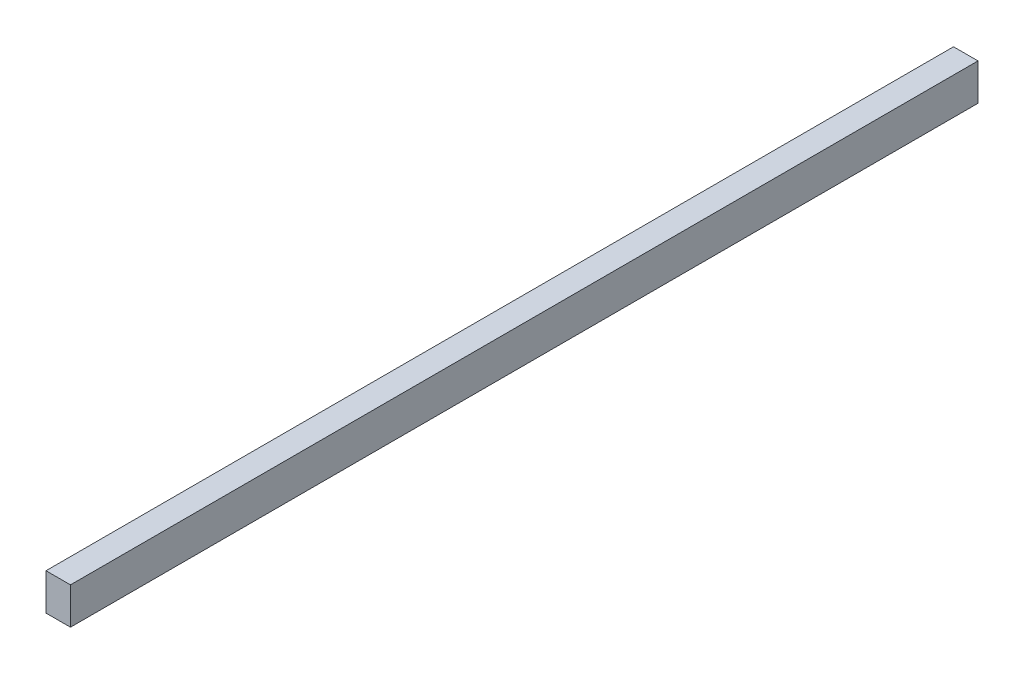
SolidWorks part; units mm, degrees
ref_plane "Front Plane" through (0, 0, 0) normal (0, 0, 1) x (1, 0, 0)
ref_plane "Top Plane" through (0, 0, 0) normal (0, 1, 0) x (1, 0, 0)
ref_plane "Right Plane" through (0, 0, 0) normal (1, 0, 0) x (0, 0, -1)
sketch "Sketch1" plane through (0, 0, 0) normal (1, 0, 0) x (0, 0, -1)
  line L1 (0, 0) -> (445, 0)
  line L2 (0, 0) -> (0, 18)
  line L3 (0, 18) -> (445, 18)
  line L4 (445, 0) -> (445, 18)
  dimension "D1" = 445
  dimension "D2" = 18
extrude "Boss-Extrude1" add sketch "Sketch1" along normal blind 12
